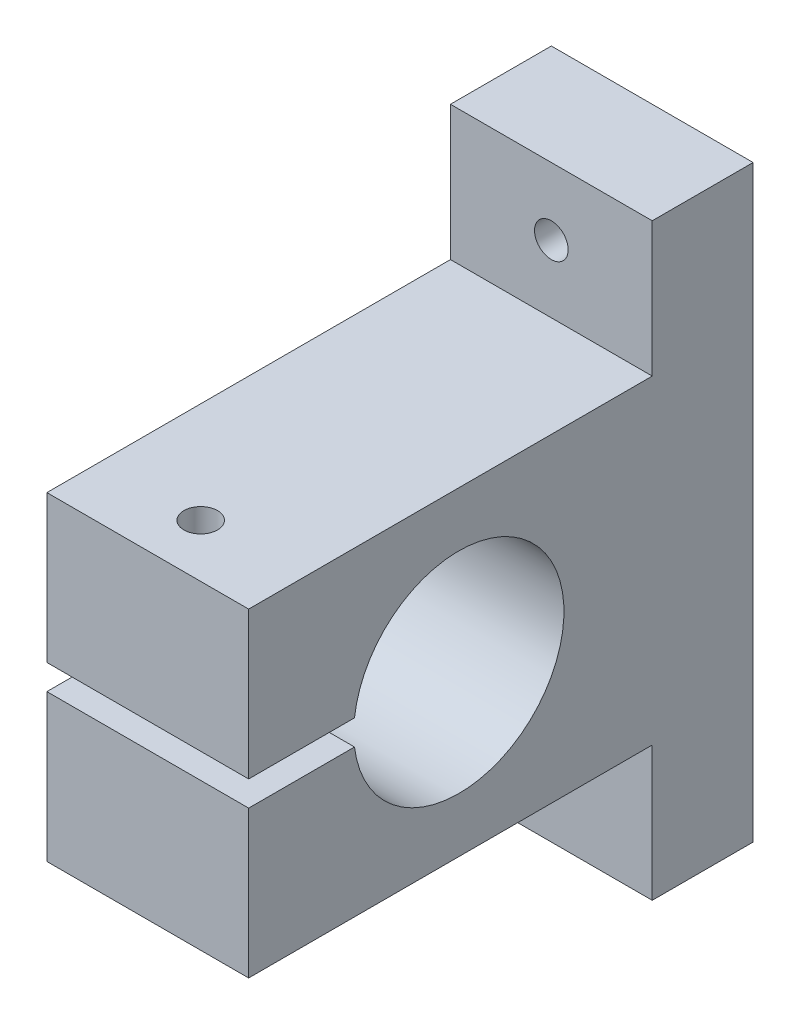
SolidWorks part; units mm, degrees
ref_plane "Top Plane" through (0, 0, 0) normal (0, 0, 1) x (1, 0, 0)
ref_plane "Right Plane" through (0, 0, 0) normal (0, 1, 0) x (1, 0, 0)
ref_plane "Front Plane" through (0, 0, 0) normal (1, 0, 0) x (0, 0, -1)
sketch "Sketch1" plane through (0, 0, 0) normal (1, 0, 0) x (0, 0, -1)
  line L0 (23, 35) -> (23, 19)
  line L1 (23, 35) -> (35, 35)
  line L2 (23, -35) -> (35, -35)
  line L3 (35, 35) -> (35, -35)
  line L5 (-25, 19) -> (23, 19)
  line L6 (-25, -19) -> (23, -19)
  line L8 (23, -19) -> (23, -35)
  line L9 (-25, -19) -> (-25, -1.5)
  line L10 (-25, -1.5) -> (-12.4097, -1.5)
  line L11 (-25, 19) -> (-25, 1.5)
  line L12 (-25, 1.5) -> (-12.4097, 1.5)
  line L13 (-25, 1.5) -> (-25, -1.5) construction
  line L14 (-25, 0) -> (0, 0) construction
  arc A0 (-12.4097, -1.5) -> (-12.4097, 1.5) centre (0, 0) ccw
  point P1 (-12.3616, -1.8553)
  dimension "D1" = 25
  dimension "D2" = 38
  dimension "D3" = 35
  dimension "D4" = 12
  dimension "D5" = 70
  dimension "D6" = 60
  dimension "D7" = 3
extrude "Boss-Extrude1" add sketch "Sketch1" along normal blind 24
sketch "Sketch2" plane through (0, 0, -23) normal (0, 0, 1) x (1, 0, 0)
  line L0 (24, -19) -> (0, -35) construction
  circle A0 centre (12, -27) radius 2
  point P6 (10, -30)
  dimension "D1" = 4
extrude "Cut-Extrude1" cut sketch "Sketch2" against normal blind 20
sketch "Sketch3" plane through (0, -19, 0) normal (0, -1, 0) x (1, 0, 0)
  line L0 (0, 25) -> (24, 12.4097) construction
  line L1 (24, 25) -> (24, -23) construction
  circle A0 centre (12, 18.7048) radius 2
  dimension "D1" = 4
extrude "Cut-Extrude2" cut sketch "Sketch3" against normal up to surface (20.5 mm away)
mirror "Mirror1" about plane through (0, 0, 0) normal (0, 1, 0) of "Cut-Extrude1", "Cut-Extrude2"
